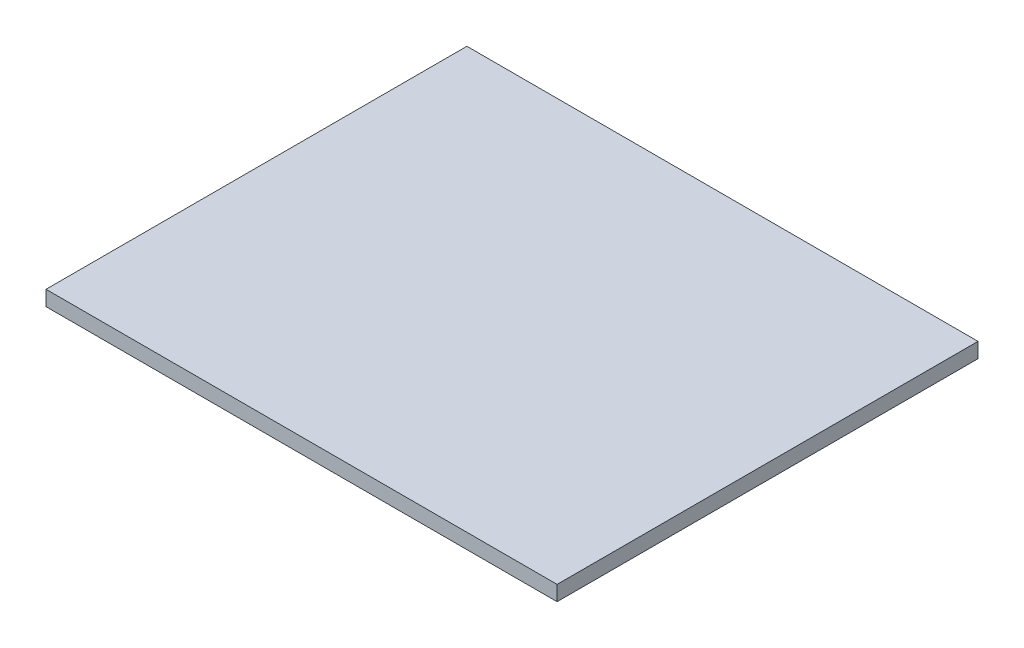
SolidWorks part; units mm, degrees
ref_plane "정면" through (0, 0, 0) normal (0, 0, 1) x (1, 0, 0)
ref_plane "윗면" through (0, 0, 0) normal (0, 1, 0) x (1, 0, 0)
ref_plane "우측면" through (0, 0, 0) normal (1, 0, 0) x (0, 0, -1)
sketch "스케치1" plane through (0, 0, 0) normal (0, 1, 0) x (1, 0, 0)
  line L1 (0, 0) -> (170, 0)
  line L2 (0, 0) -> (0, 140)
  line L3 (0, 140) -> (170, 140)
  line L4 (170, 0) -> (170, 140)
  dimension "D1" = 170
  dimension "D2" = 140
extrude "보스-돌출1" add sketch "스케치1" along normal blind 5
hole_wizard "M4 여유 구멍1" positions "스케치3" profile "스케치2" hole size "M4" standard "Ansi Metric"
sketch "스케치3" plane through (0, 3, 0) normal (0, 1, 0) x (1, 0, 0)
  line L9 (0, 0) -> (120, 0) construction
  line L10 (111.9615, 95) -> (8.0385, 95) construction
  line L11 (8.0385, 95) -> (60, 5) construction
  line L12 (60, 5) -> (111.9615, 95) construction
  line L15 (120, 100) -> (0, 100) construction
  line L16 (60, 95) -> (60, 100) construction
  point P0 (8.0385, 95)
  point P2 (111.9615, 95)
  point P4 (60, 5)
  dimension "D1" = 5
  dimension "D2" = 5
sketch "스케치2" plane through (8.0385, 3, -95) normal (1, 0, 0) x (0, 0, 1)
  line L0 (0, 0) -> (0, 21.3519)
  line L1 (0, 21.3519) -> (2.25, 20)
  line L2 (2.25, 20) -> (2.25, 0)
  line L5 (2.25, 0) -> (0, 0)
  line L10 (0, 21.3519) -> (-2.25, 20) construction
  line L11 (0, -6.35) -> (0, 107.95) construction
  dimension "구멍 지름" = 4.5
  dimension "구멍 깊이" = 20
  dimension "드릴 각도" = 118
